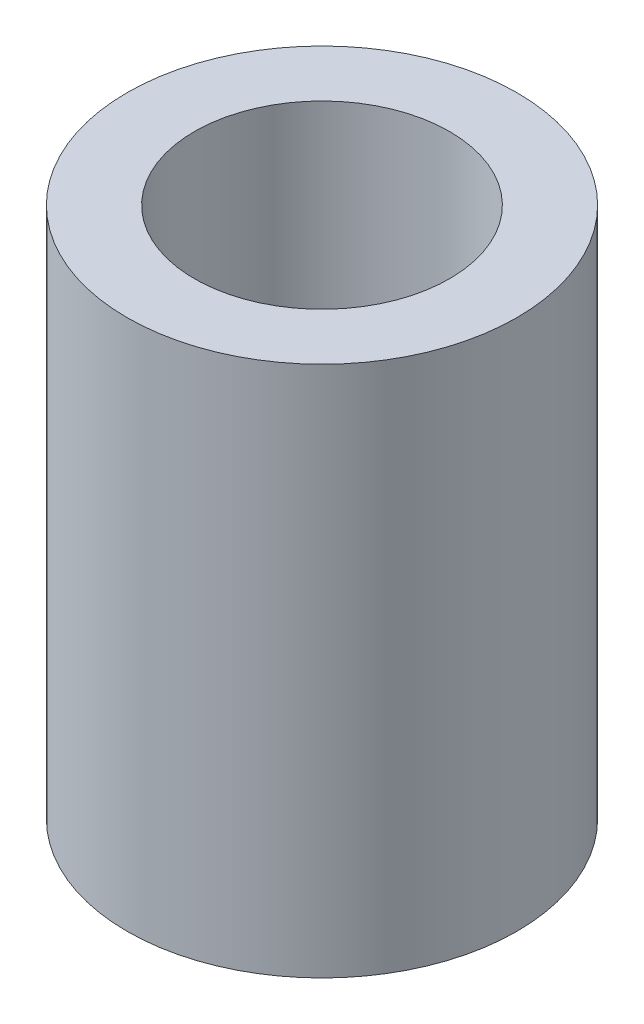
SolidWorks part; units mm, degrees
ref_plane "Front Plane" through (0, 0, 0) normal (0, 0, 1) x (1, 0, 0)
ref_plane "Top Plane" through (0, 0, 0) normal (0, 1, 0) x (1, 0, 0)
ref_plane "Right Plane" through (0, 0, 0) normal (1, 0, 0) x (0, 0, -1)
sketch "Sketch1" plane through (0, 0, 0) normal (0, 0, 1) x (1, 0, 0)
  line L0 (0, 0) -> (0, 60) construction
  line L2 (14.4, 0) -> (22, 0)
  line L3 (14.4, 0) -> (14.4, 60)
  line L4 (14.4, 60) -> (22, 60)
  line L5 (22, 0) -> (22, 60)
  dimension "D1" = 60
  dimension "D2" = 22
  dimension "D3" = 14.4
revolve "Revolve1" add sketch "Sketch1" angle 360 about L0
